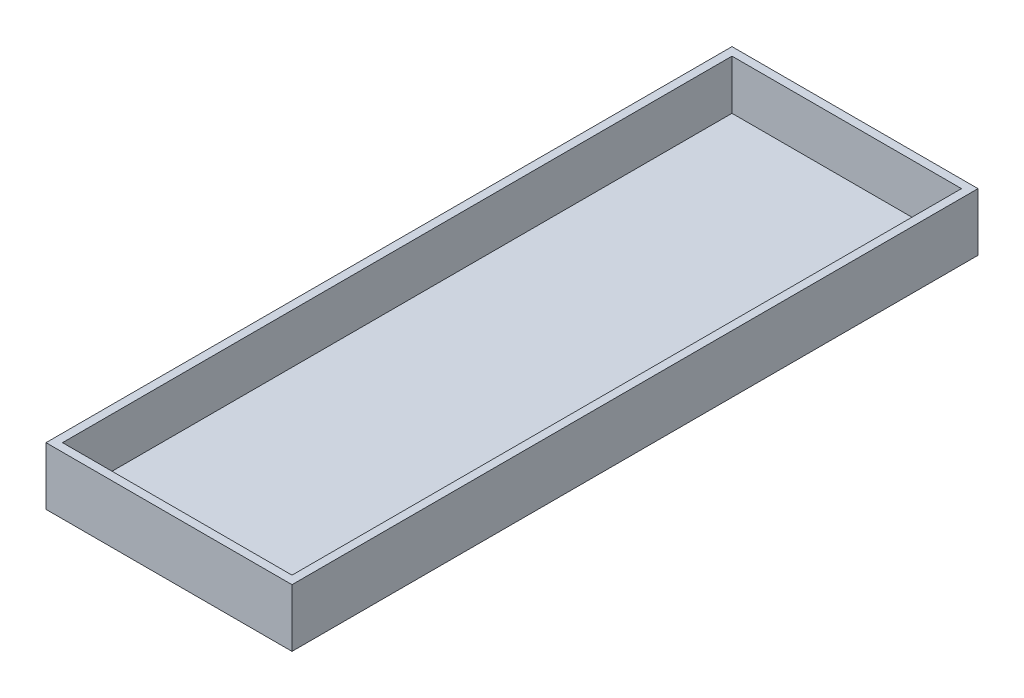
SolidWorks part; units mm, degrees
ref_plane "Front Plane" through (0, 0, 0) normal (0, 0, 1) x (1, 0, 0)
ref_plane "Top Plane" through (0, 0, 0) normal (0, 1, 0) x (1, 0, 0)
ref_plane "Right Plane" through (0, 0, 0) normal (1, 0, 0) x (0, 0, -1)
sketch "Sketch1" plane through (0, 0, 0) normal (0, 0, 1) x (1, 0, 0)
  line L1 (-137.8161, 35.2103) -> (-78.2161, 35.2103)
  line L2 (-137.8161, 35.2103) -> (-137.8161, 21.2103)
  line L3 (-137.8161, 21.2103) -> (-78.2161, 21.2103)
  line L4 (-78.2161, 35.2103) -> (-78.2161, 21.2103)
extrude "Boss-Extrude1" add sketch "Sketch1" along normal blind 166.2
sketch "Sketch5" plane through (0, 35.2103, 0) normal (0, 1, 0) x (1, 0, 0)
  line L0 (-137.8161, 0) -> (-135.8161, 0) construction
  line L1 (-78.2161, 0) -> (-137.8161, 0) construction
  line L2 (-78.2161, 0) -> (-80.2161, 0) construction
  line L3 (-137.8161, -166.2) -> (-135.8161, -166.2) construction
  line L4 (-78.2161, -166.2) -> (-137.8161, -166.2) construction
  line L5 (-78.2161, -166.2) -> (-80.2161, -166.2) construction
  line L6 (-80.2161, -166.2) -> (-80.2161, -164.2) construction
  line L7 (-135.8161, -166.2) -> (-135.8161, -164.2)
  line L8 (-135.8161, 0) -> (-135.8161, -2)
  line L9 (-80.2161, 0) -> (-80.2161, -2)
  line L11 (-135.8161, -2) -> (-80.2161, -2)
  line L12 (-135.8161, -2) -> (-135.8161, -164.2)
  line L13 (-135.8161, -164.2) -> (-80.2161, -164.2)
  line L14 (-80.2161, -2) -> (-80.2161, -164.2)
extrude "Cut-Extrude2" cut sketch "Sketch5" against normal blind 12 contours L12 L11 L14 L13
